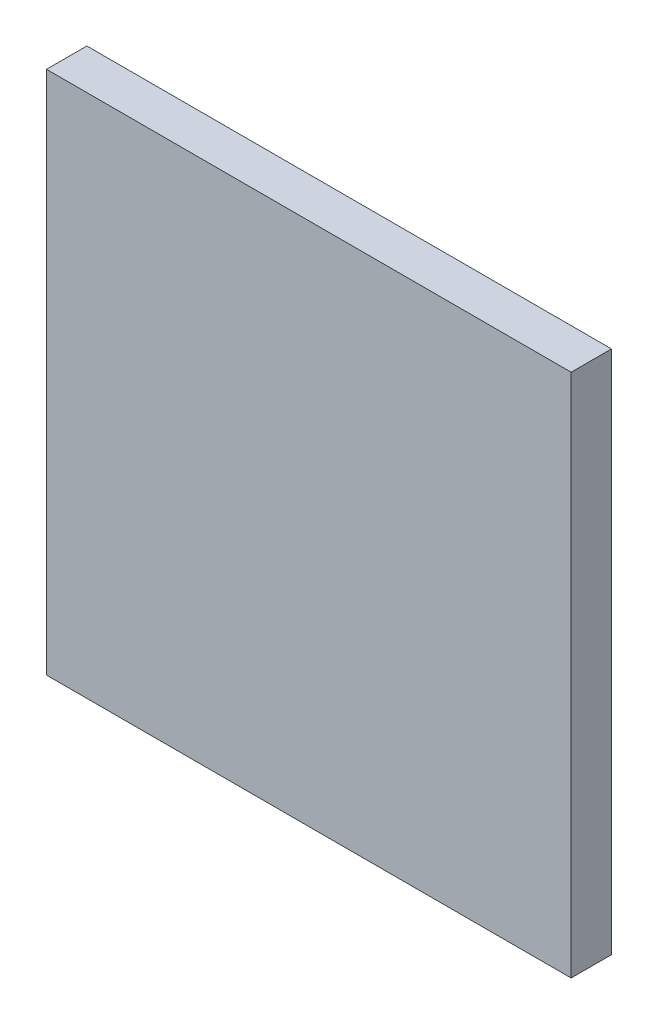
SolidWorks part; units mm, degrees
ref_plane "前视基准面" through (0, 0, 0) normal (0, 0, 1) x (1, 0, 0)
ref_plane "上视基准面" through (0, 0, 0) normal (0, 1, 0) x (1, 0, 0)
ref_plane "右视基准面" through (0, 0, 0) normal (1, 0, 0) x (0, 0, -1)
sketch "草图1" plane through (0, 0, 0) normal (0, 0, 1) x (1, 0, 0)
  line L1 (-32.5, -32.5) -> (32.5, -32.5)
  line L2 (-32.5, -32.5) -> (-32.5, 32.5)
  line L3 (-32.5, 32.5) -> (32.5, 32.5)
  line L4 (32.5, -32.5) -> (32.5, 32.5)
  line L5 (-32.5, -32.5) -> (32.5, 32.5) construction
  line L6 (-32.5, 32.5) -> (32.5, -32.5) construction
  point P0 (0, 0)
extrude "凸台-拉伸1" add sketch "草图1" along normal blind 5
